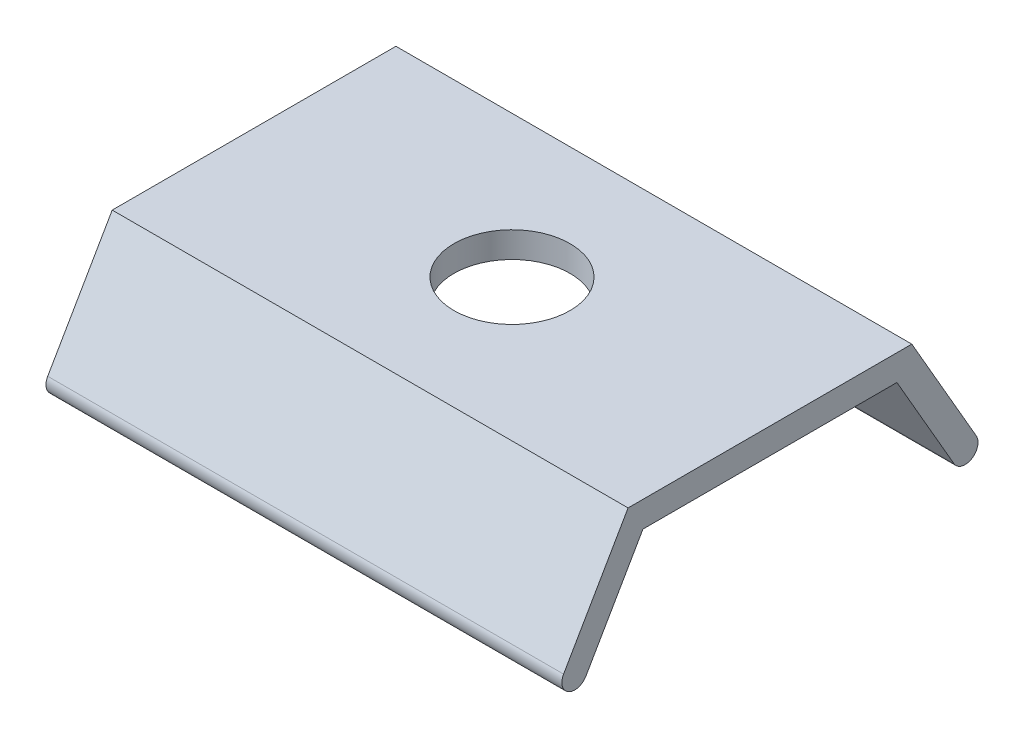
SolidWorks part; units mm, degrees
ref_plane "Front Plane" through (0, 0, 0) normal (0, 0, 1) x (1, 0, 0)
ref_plane "Top Plane" through (0, 0, 0) normal (0, 1, 0) x (1, 0, 0)
ref_plane "Right Plane" through (0, 0, 0) normal (1, 0, 0) x (0, 0, -1)
sketch "Sketch1" plane through (0, 0, 0) normal (1, 0, 0) x (0, 0, -1)
  line L0 (-5.5, 0) -> (5.5, 0)
  line L1 (-5.5, 0) -> (-8, -4.3301)
  line L2 (5.5, 0) -> (8, -4.3301)
  line L3 (-4.9226, -1) -> (-7.134, -4.8301)
  line L4 (-4.9226, -1) -> (4.9226, -1)
  line L5 (4.9226, -1) -> (7.134, -4.8301)
  arc A0 (-8, -4.3301) -> (-7.134, -4.8301) centre (-7.567, -4.5801) ccw
  arc A1 (8, -4.3301) -> (7.134, -4.8301) centre (7.567, -4.5801) cw
  point P4 (0, 0)
  dimension "D1" = 16
  dimension "D2" = 5
  dimension "D3" = 120
  dimension "D4" = 120
  dimension "D5" = 1
extrude "Boss-Extrude1" add sketch "Sketch1" along normal mid plane 20
hole_wizard "M4 Clearance Hole1" positions "Sketch2" profile "Sketch3" hole size "M4" standard "ISO" end condition through all
sketch "Sketch2" plane through (0, 0, 0) normal (0, 1, 0) x (1, 0, 0)
  point P0 (0, 0)
sketch "Sketch3" plane through (0, 0, 0) normal (1, 0, 0) x (0, 0, 1)
  line L0 (0, 0) -> (0, 5.0801)
  line L1 (0, 5.0801) -> (2.25, 5.0801)
  line L2 (2.25, 5.0801) -> (2.25, 0)
  line L5 (2.25, 0) -> (0, 0)
  line L11 (0, -6.35) -> (0, 107.95) construction
  dimension "Thru Hole Dia." = 4.5
  dimension "Thru Hole Depth" = 5.0801
